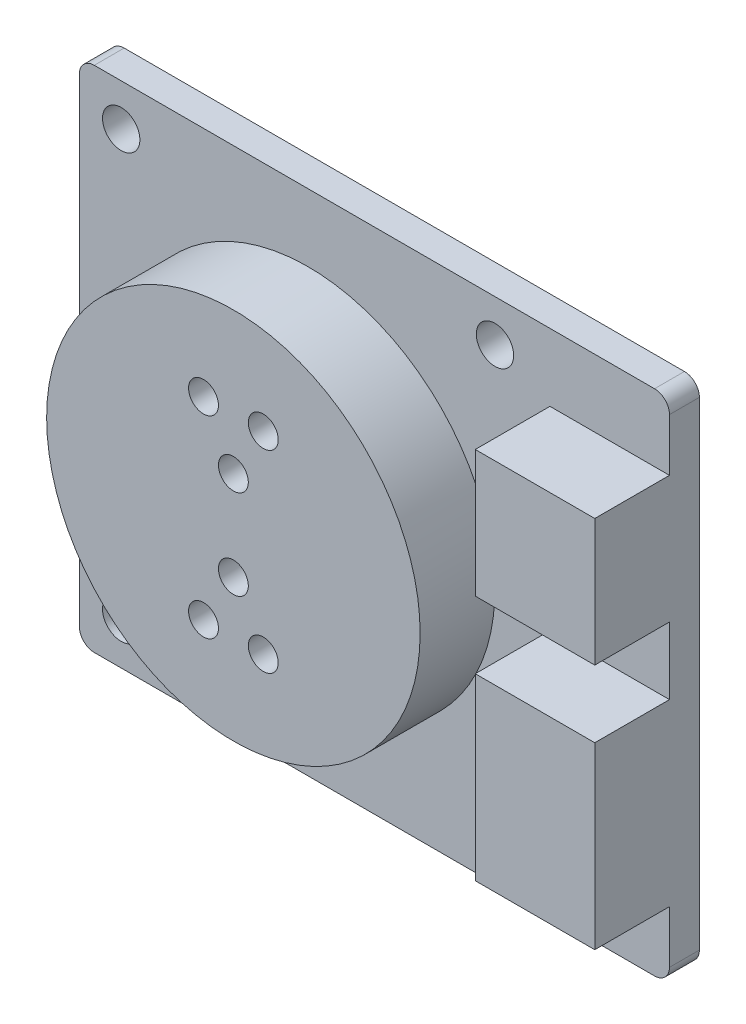
SolidWorks part; units mm, degrees
material "AISI 304"
ref_plane "前视基准面" through (0, 0, 0) normal (0, 0, 1) x (1, 0, 0)
ref_plane "上视基准面" through (0, 0, 0) normal (0, 1, 0) x (1, 0, 0)
ref_plane "右视基准面" through (0, 0, 0) normal (1, 0, 0) x (0, 0, -1)
other "Configuration Table"
sketch "草图1" plane through (0, 0, 0) normal (0, 0, 1) x (1, 0, 0)
  line L1 (-19.75, -17.02) -> (19.75, -17.02)
  line L2 (-19.75, -17.02) -> (-19.75, 17.02)
  line L3 (-19.75, 17.02) -> (19.75, 17.02)
  line L4 (19.75, -17.02) -> (19.75, 17.02)
  line L5 (-19.75, -17.02) -> (19.75, 17.02) construction
  line L6 (-19.75, 17.02) -> (19.75, -17.02) construction
  point P0 (0, 0)
  dimension "D1" = 39.5
  dimension "D2" = 34.04
extrude "凸台-拉伸1" add sketch "草图1" along normal blind 2
sketch "草图2" plane through (0, 0, 2) normal (0, 0, 1) x (1, 0, 0)
  line L0 (-16.95, 14.225) -> (-16.95, -14.225) construction
  line L1 (-16.95, -14.225) -> (8.07, -14.225) construction
  line L2 (8.07, -14.225) -> (8.07, 14.225) construction
  line L3 (8.07, 14.225) -> (-16.95, 14.225) construction
  line L6 (-16.95, 0) -> (0, 0) construction
  line L8 (-19.75, 17.02) -> (-19.75, -17.02) construction
  circle A0 centre (-16.95, 14.225) radius 1.25
  circle A1 centre (-16.95, -14.225) radius 1.25
  circle A2 centre (8.07, 14.225) radius 1.25
  circle A3 centre (8.07, -14.225) radius 1.25
  dimension "D1" = 2.5
  dimension "D2" = 28.45
  dimension "D4" = 2.8
  dimension "D3" = 25.02
extrude "切除-拉伸1" cut sketch "草图2" against normal blind 2
sketch "草图3" plane through (0, 0, 2) normal (0, 0, 1) x (1, 0, 0)
  line L0 (-16.95, 14.225) -> (8.07, -14.225) construction
  circle A0 centre (-4.44, 0) radius 12.5
  dimension "D1" = 25
extrude "凸台-拉伸2" add sketch "草图3" along normal blind 5
fillet "圆角1" radius 1 4 edges at (-19.75, -17.02, 1) (19.75, -17.02, 1) (19.75, 17.02, 1) (-19.75, 17.02, 1)
sketch "草图4" plane through (0, 0, 2) normal (0, 0, 1) x (1, 0, 0)
  line L0 (19.75, -16.02) -> (19.75, 16.02) construction
  line L1 (19.75, 12.5) -> (11.75, 12.5)
  line L2 (19.75, 12.5) -> (19.75, 4)
  line L3 (19.75, 4) -> (11.75, 4)
  line L4 (11.75, 12.5) -> (11.75, 4)
  line L6 (19.75, -0.5) -> (11.75, -0.5)
  line L7 (19.75, -0.5) -> (19.75, -12.5)
  line L8 (19.75, -12.5) -> (11.75, -12.5)
  line L9 (11.75, -0.5) -> (11.75, -12.5)
  circle A1 centre (-4.44, 0) radius 12.5 construction
  circle A2 centre (-4.44, 0) radius 12.5 construction
  dimension "D1" = 8.5
  dimension "D2" = 12
  dimension "D3" = 8
extrude "凸台-拉伸3" add sketch "草图4" along normal blind 5
sketch "草图5" plane through (0, 0, 7) normal (0, 0, 1) x (1, 0, 0)
  line L0 (-6.44, 6.4641) -> (-4.44, 3) construction
  line L1 (-4.44, 3) -> (-2.44, 6.4641) construction
  line L2 (-2.44, 6.4641) -> (-6.44, 6.4641) construction
  line L3 (-16.94, 0) -> (8.06, 0) construction
  line L4 (-2.44, -6.4641) -> (-6.44, -6.4641) construction
  line L5 (-4.44, -3) -> (-2.44, -6.4641) construction
  line L6 (-6.44, -6.4641) -> (-4.44, -3) construction
  line L7 (-4.44, 3) -> (-4.44, 0) construction
  circle A0 centre (-6.44, 6.4641) radius 1
  circle A1 centre (-2.44, 6.4641) radius 1
  circle A2 centre (-4.44, 3) radius 1
  circle A3 centre (-4.44, 0) radius 12.5 construction
  circle A4 centre (-4.44, 0) radius 12.5 construction
  circle A5 centre (-4.44, -3) radius 1
  circle A6 centre (-2.44, -6.4641) radius 1
  circle A7 centre (-6.44, -6.4641) radius 1
  dimension "D1" = 2
  dimension "D2" = 4
  dimension "D3" = 3
extrude "切除-拉伸2" cut sketch "草图5" against normal up to surface (5 mm away) up to face at (-16.94, 0, 2)
